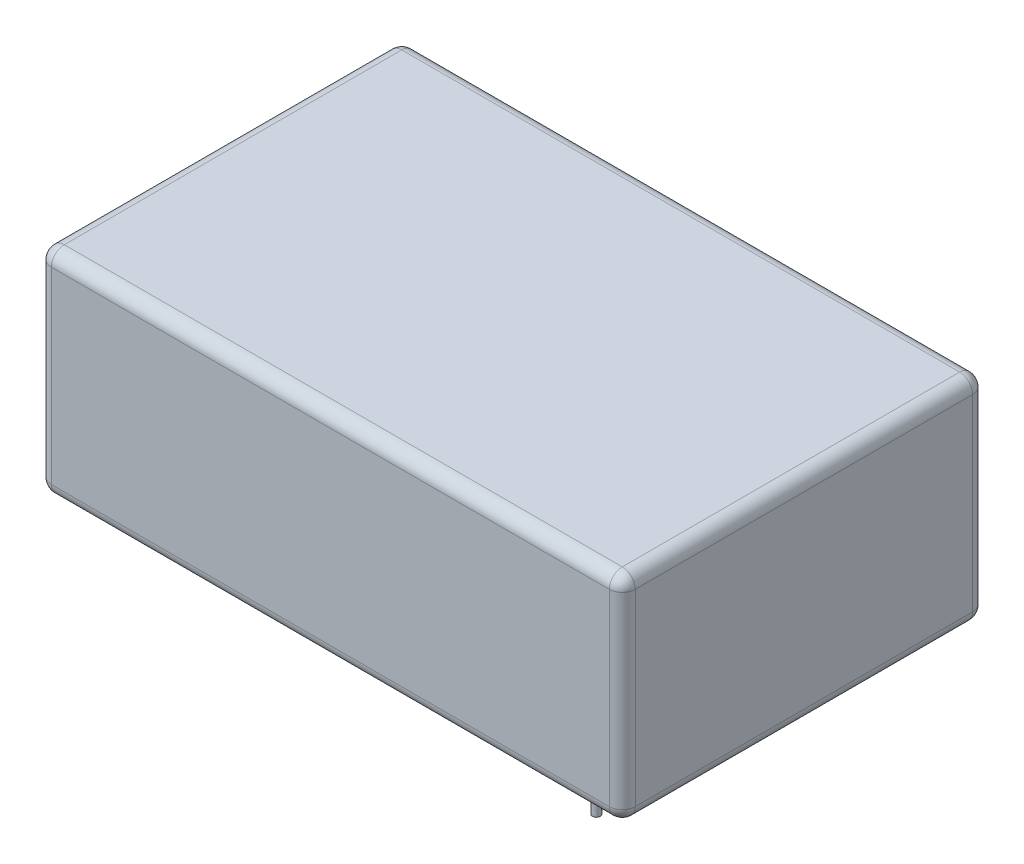
SolidWorks part; units mm, degrees
ref_plane "Front Plane" through (0, 0, 0) normal (0, 0, 1) x (1, 0, 0)
ref_plane "Top Plane" through (0, 0, 0) normal (0, 1, 0) x (1, 0, 0)
ref_plane "Right Plane" through (0, 0, 0) normal (1, 0, 0) x (0, 0, -1)
sketch "Sketch1" plane through (0, 0, 0) normal (0, 0, 1) x (1, 0, 0)
  line L1 (0, 0) -> (45, 0)
  line L2 (0, 0) -> (0, 16.5)
  line L3 (0, 16.5) -> (45, 16.5)
  line L4 (45, 0) -> (45, 16.5)
  dimension "D1" = 16.5
  dimension "D2" = 45
extrude "Boss-Extrude1" add sketch "Sketch1" along normal blind 28
sketch "Sketch2" plane through (0, 0, 0) normal (0, -1, 0) x (-1, 0, 0)
  line L0 (0, -28) -> (0, 0) construction
  line L1 (0, -28) -> (-45, -28) construction
  line L2 (-39, -28) -> (-39, 0) construction
  line L3 (0, 0) -> (-45, 0) construction
  line L4 (-45, -28) -> (-45, 0) construction
  circle A0 centre (-6, -19) radius 0.3
  circle A1 centre (-6, -9) radius 0.3
  circle A2 centre (-39, -24) radius 0.3
  circle A4 centre (-39, -4) radius 0.3
  dimension "D1" = 0.6
  dimension "D2" = 0.6
  dimension "D8" = 0.6
  dimension "D9" = 0.6
  dimension "D3" = 6
  dimension "D4" = 9
  dimension "D5" = 6
  dimension "D6" = 10
  dimension "D7" = 6
  dimension "D10" = 20
  dimension "D11" = 4
extrude "Boss-Extrude2" add sketch "Sketch2" along normal blind 4
fillet "Fillet1" radius 1 16 edges at (6, 0, 19.3) (6, 0, 9.3) (39, 0, 24.3) (39, 0, 4.3) (45, 0, 14) (22.5, 0, 0) (45, 8.25, 0) (0, 0, 14) (0, 8.25, 0) (45, 8.25, 28) (22.5, 0, 28) (0, 8.25, 28) (45, 16.5, 14) (22.5, 16.5, 28) (0, 16.5, 14) (22.5, 16.5, 0)
